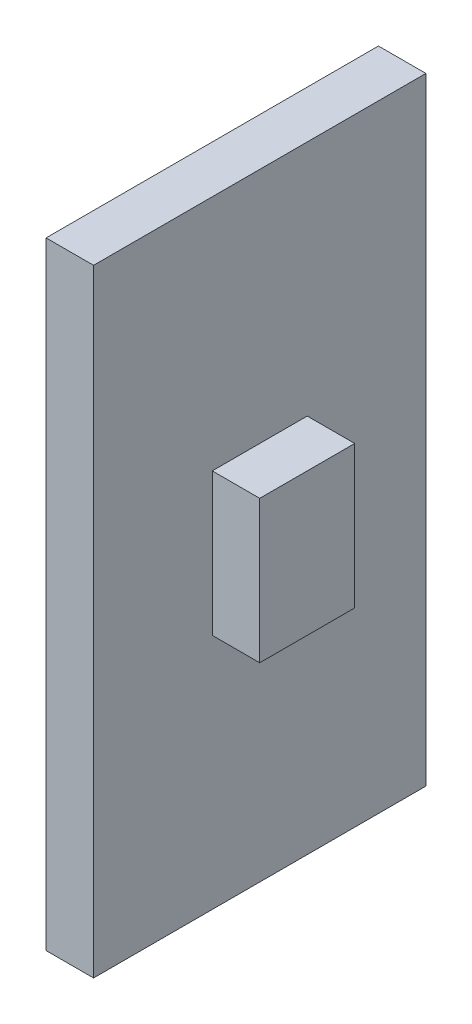
SolidWorks part; units mm, degrees
ref_plane "Front Plane" through (0, 0, 0) normal (0, 0, 1) x (1, 0, 0)
ref_plane "Top Plane" through (0, 0, 0) normal (0, 1, 0) x (1, 0, 0)
ref_plane "Right Plane" through (0, 0, 0) normal (1, 0, 0) x (0, 0, -1)
sketch "Croquis1" plane through (0, 0, 0) normal (1, 0, 0) x (0, 0, -1)
  line L1 (-3.5, -7.6333) -> (3.5, -7.6333)
  line L2 (-3.5, -7.6333) -> (-3.5, 5.3667)
  line L3 (-3.5, 5.3667) -> (3.5, 5.3667)
  line L4 (3.5, -7.6333) -> (3.5, 5.3667)
  point P0 (0, 0)
  dimension "D1" = 7
  dimension "D2" = 13
extrude "Saliente-Extruir1" add sketch "Croquis1" along normal blind 1
sketch "Croquis2" plane through (1, 0, 0) normal (1, 0, 0) x (0, 0, -1)
  line L7 (-1, 0.3667) -> (1, 0.3667)
  line L8 (-1, 0.3667) -> (-1, -2.6333)
  line L9 (-1, -2.6333) -> (1, -2.6333)
  line L10 (1, 0.3667) -> (1, -2.6333)
  point P12 (0, -1.1333)
extrude "Saliente-Extruir2" add sketch "Croquis2" along normal blind 1 separate body
